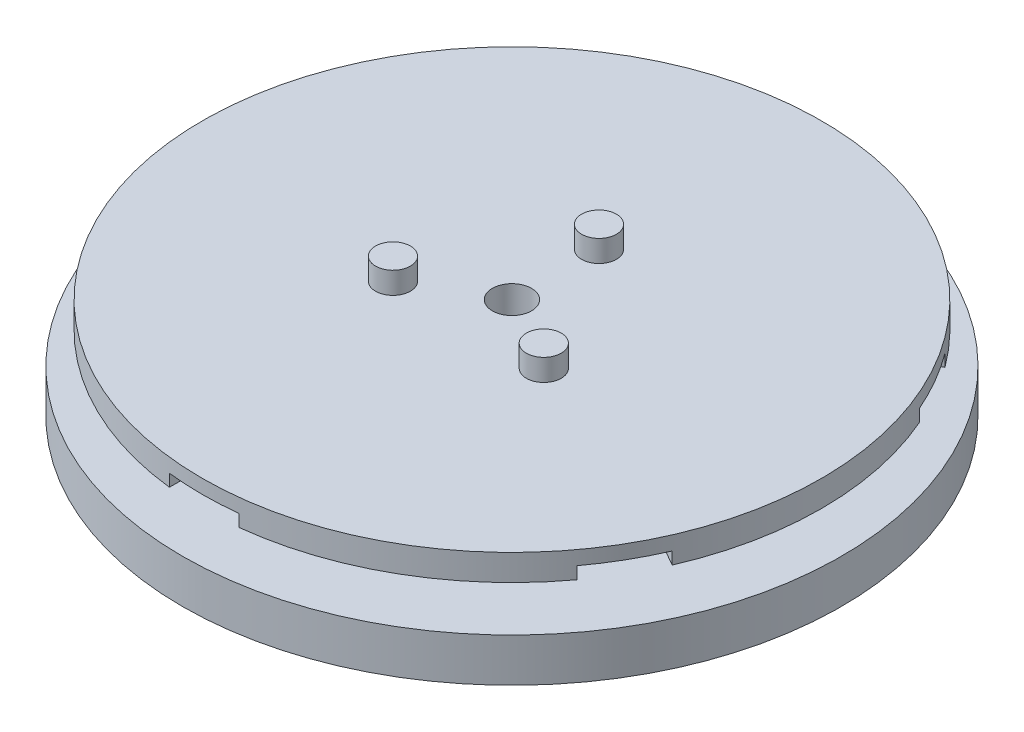
SolidWorks part; units mm, degrees
material "ABS"
ref_plane "Front Plane" through (0, 0, 0) normal (0, 0, 1) x (1, 0, 0)
ref_plane "Top Plane" through (0, 0, 0) normal (0, 1, 0) x (1, 0, 0)
ref_plane "Right Plane" through (0, 0, 0) normal (1, 0, 0) x (0, 0, -1)
sketch "Sketch1" plane through (0, 0, 0) normal (0, 1, 0) x (1, 0, 0)
  circle A0 centre (0, 0) radius 37.846
  dimension "D1" = 75.692
extrude "Boss-Extrude1" add sketch "Sketch1" along normal blind 5
sketch "Sketch2" plane through (0, 5, 0) normal (0, 1, 0) x (1, 0, 0)
  circle A0 centre (0, 0) radius 24.846
  circle A1 centre (0, 0) radius 37.846 construction
  dimension "D1" = 13
extrude "Boss-Extrude2" add sketch "Sketch2" along normal blind 5
sketch "Sketch3" plane through (0, 10, 0) normal (0, 1, 0) x (1, 0, 0)
  circle A0 centre (0, 0) radius 35.56
  dimension "D1" = 71.12
extrude "Boss-Extrude3" add sketch "Sketch3" along normal blind 1.6
sketch "Sketch4" plane through (0, 11.6, 0) normal (0, 1, 0) x (1, 0, 0)
  line L0 (0, 35.56) -> (0, -35.56) construction
  line L1 (-35.56, 0) -> (35.56, 0) construction
  circle A0 centre (0, 0) radius 35.56 construction
  circle A1 centre (0, 10) radius 2
  dimension "D2" = 4
  dimension "D1" = 10
extrude "Boss-Extrude4" add sketch "Sketch4" along normal blind 2.5
pattern_circular "CirPattern1" count 3 over 360 about axis through (0, 0, 0) along (0, 1, 0) of "Boss-Extrude4"
hole_wizard "CSK for #8 Flat Head Machine Screw (100)1" positions "Sketch5" profile "Sketch6" countersink size "#8" standard "ANSI Inch" end condition through all
sketch "Sketch5" plane through (0, 0, 0) normal (0, -1, 0) x (-1, 0, 0)
  point P0 (0, 0)
sketch "Sketch6" plane through (0, 0, 0) normal (1, 0, 0) x (0, 0, -1)
  line L0 (0, 0) -> (0, 14.1)
  line L1 (0, 14.1) -> (2.2479, 14.1)
  line L2 (2.2479, 14.1) -> (2.2479, 1.6518)
  line L3 (2.2479, 1.6518) -> (4.2164, 0)
  line L5 (4.2164, 0) -> (0, 0)
  line L6 (-2.2479, 1.6518) -> (-4.2164, 0) construction
  line L11 (0, -6.35) -> (0, 107.95) construction
  dimension "Thru Hole Dia." = 4.4958
  dimension "Thru Hole Depth" = 14.1
  dimension "Near C'Sink Dia." = 8.4328
  dimension "Near C'Sink Angle" = 100
sketch "Sketch7" plane through (0, 11.6, 0) normal (0, 1, 0) x (1, 0, 0)
  circle A0 centre (0, 0) radius 35.56
  circle A1 centre (0, 0) radius 35.56 construction
extrude "Boss-Extrude5" add sketch "Sketch7" against normal blind 3
sketch "Sketch8" plane through (0, 11.6, 0) normal (0, 1, 0) x (1, 0, 0)
  line L0 (0, 35.56) -> (0, -35.56) construction
  line L1 (-4, 35.56) -> (-4, 23.56)
  line L2 (-4, 35.56) -> (4, 35.56)
  line L4 (-4, 23.56) -> (4, 23.56)
  line L5 (4, 35.56) -> (4, 23.56)
  circle A0 centre (0, 0) radius 35.56 construction
  dimension "D1" = 12
extrude "Cut-Extrude1" cut sketch "Sketch8" against normal up to surface (1.4 mm away) from offset 1.6 up to face at (0, 8.6, 35.56) offset against normal yes
pattern_circular "CirPattern2" count 6 over 360 about axis through (0, 0, 0) along (0, 1, 0) of "Cut-Extrude1"
sketch "Sketch9" plane through (0, 8.6, 0) normal (0, -1, 0) x (1, 0, 0)
  circle A0 centre (0, 0) radius 2.2479
  circle A1 centre (0, 0) radius 2.2479 construction
extrude "Cut-Extrude2" cut sketch "Sketch9" against normal through all
